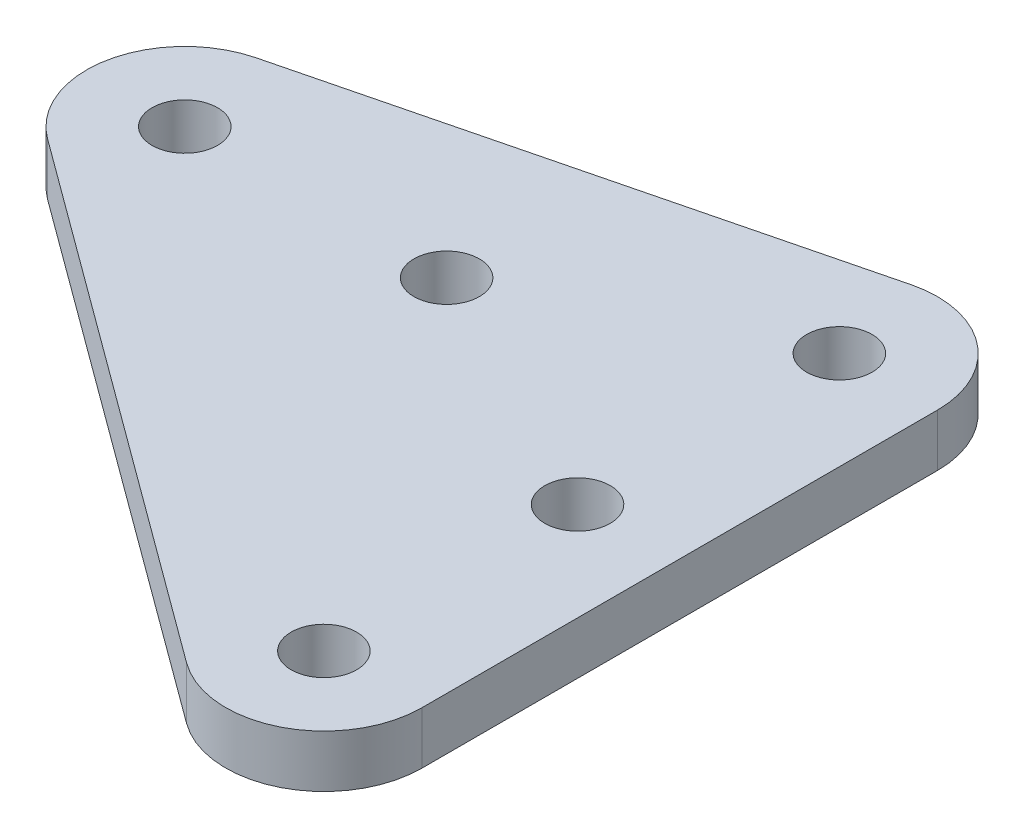
SolidWorks part; units mm, degrees
material "Thornel VCB-20 Carbon Cloth"
ref_plane "Front Plane" through (0, 0, 0) normal (0, 0, 1) x (1, 0, 0)
ref_plane "Top Plane" through (0, 0, 0) normal (0, 1, 0) x (1, 0, 0)
ref_plane "Right Plane" through (0, 0, 0) normal (1, 0, 0) x (0, 0, -1)
sketch "Sketch1" plane through (0, 0, 0) normal (0, 1, 0) x (1, 0, 0)
  line L0 (-36.3695, 9.6876) -> (36.3695, 9.6876) construction
  line L1 (-28.279, 16.9636) -> (11.721, 26.9636)
  line L2 (21.04, 19.6876) -> (21.04, -19.6876)
  line L3 (-30.8993, 3.6425) -> (9.1007, -25.7326)
  circle A0 centre (-26.46, 9.6876) radius 2.5
  circle A1 centre (-6.46, 9.6876) radius 2.5
  circle A2 centre (13.54, 19.6876) radius 2.5
  circle A3 centre (13.54, -0.3124) radius 2.5
  arc A4 (-28.279, 16.9636) -> (-30.8993, 3.6425) centre (-26.46, 9.6876) ccw
  arc A5 (21.04, 19.6876) -> (11.721, 26.9636) centre (13.54, 19.6876) ccw
  arc A6 (9.1007, -25.7326) -> (21.04, -19.6876) centre (13.54, -19.6876) ccw
  circle A7 centre (13.54, -19.6876) radius 2.5
  dimension "D1" = 5
  dimension "D2" = 5
  dimension "D5" = 5
  dimension "D3" = 10
  dimension "D4" = 20
extrude "Boss-Extrude1" add sketch "Sketch1" along normal blind 4
